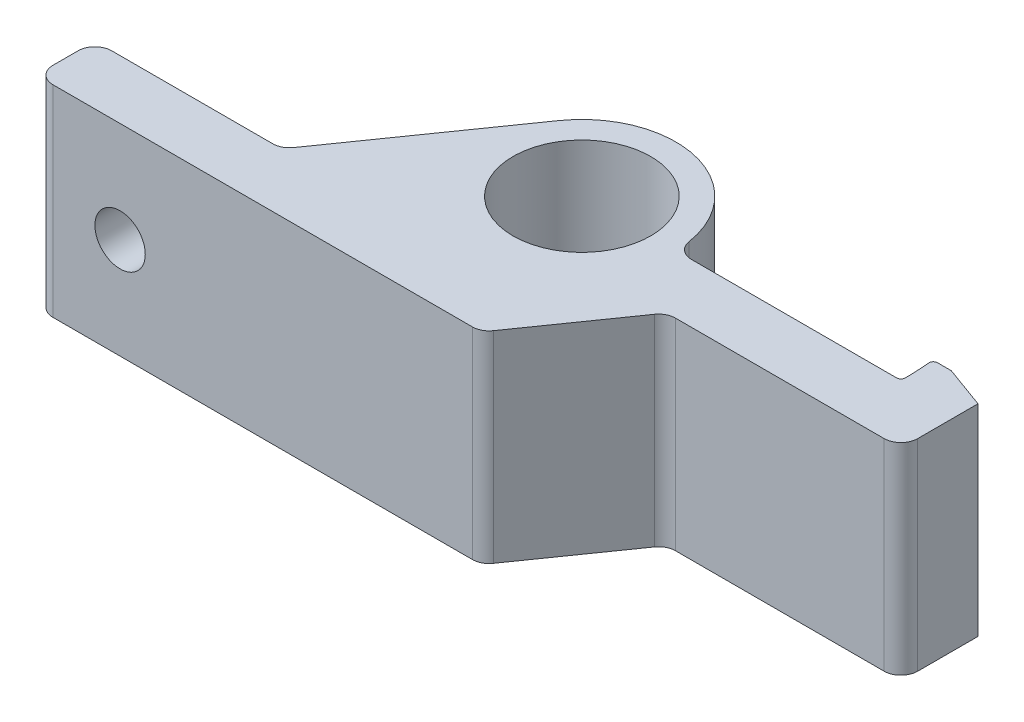
SolidWorks part; units mm, degrees
ref_plane "Front Plane" through (0, 0, 0) normal (0, 0, 1) x (1, 0, 0)
ref_plane "Top Plane" through (0, 0, 0) normal (0, 1, 0) x (1, 0, 0)
ref_plane "Right Plane" through (0, 0, 0) normal (1, 0, 0) x (0, 0, -1)
sketch "Sketch1" plane through (0, 0, 0) normal (0, 1, 0) x (1, 0, 0)
  line L0 (0, 0) -> (26.5, 0)
  line L1 (45, 6.5) -> (45, 12)
  line L2 (45, 12) -> (41.5, 12)
  line L3 (41.5, 12) -> (41.5, 10)
  line L6 (41.5, 10) -> (28.1, 10)
  line L8 (11.1123, 3.5) -> (0, 3.5)
  line L9 (0, 3.5) -> (0, 0)
  line L10 (11.1123, 3.5) -> (17.9127, 13.212)
  line L12 (26.5, 0) -> (31.0513, 6.5)
  line L13 (31.0513, 6.5) -> (45, 6.5)
  circle A0 centre (22.5, 10) radius 4.1
  arc A1 (28.1, 10) -> (17.9127, 13.212) centre (22.5, 10) ccw
  dimension "D3" = 8.2
  dimension "D7" = 125
  dimension "D8" = 3.5
  dimension "D5" = 1.5
  dimension "D2" = 3.5
  dimension "D4" = 10
  dimension "D6" = 3.5
  dimension "D9" = 125
  dimension "D10" = 4
  dimension "D11" = 45
  dimension "D12" = 22.5
  dimension "D14" = 2
extrude "Boss-Extrude1" add sketch "Sketch1" along normal mid plane 12 contours L1 L2 L3 L6 A1 L10 L8 L9 L0 L12 L13 | A0
hole_wizard "Ø3.0mm Dowel Hole1" positions "Sketch2" profile "Sketch3" hole size "Ø3.0" standard "ANSI Metric"
sketch "Sketch2" plane through (0, 0, 0) normal (0, 0, 1) x (1, 0, 0)
  line L0 (0, 6) -> (0, -6) construction
  point P0 (5, 0)
  point P5 (0, 0)
  dimension "D1" = 5
sketch "Sketch3" plane through (5, 0, 0) normal (1, 0, 0) x (0, -1, 0)
  line L0 (0, 0) -> (0, 4.4003)
  line L1 (0, 4.4003) -> (1.5, 3.499)
  line L2 (1.5, 3.499) -> (1.5, 0)
  line L5 (1.5, 0) -> (0, 0)
  line L10 (0, 4.4003) -> (-1.5, 3.499) construction
  line L11 (0, -6.35) -> (0, 107.95) construction
  dimension "Hole Dia." = 3
  dimension "Hole Depth" = 3.499
  dimension "Drill Angle" = 118
sketch "Sketch5" plane through (0, 6, 0) normal (0, 1, 0) x (1, 0, 0)
  line L0 (41.5, 12) -> (41.5, 10.5)
  line L1 (41.5, 12) -> (41.5, 10) construction
  line L2 (41.5, 12) -> (41.4011, 12)
  arc A0 (41.5, 10.5) -> (41.4011, 12) centre (22.5, 10) ccw
  dimension "D1" = 1.5
extrude "Boss-Extrude3" add sketch "Sketch5" against normal up to surface (12 mm away) up to face at (26.2595, -6, -7.3588)
fillet "Fillet1" radius 0.25 2 edges at (41.4011, 0, -12) (41.5, 0, -10)
fillet "Fillet3" radius 1 7 edges at (0, 0, -3.5) (0, 0, 0) (45, 0, -6.5) (31.0513, 0, -6.5) (26.5, 0, 0) (11.1123, 0, -3.5) (28.1, 0, -10)
sketch "Sketch8" plane through (0, 6, 0) normal (0, 1, 0) x (1, 0, 0)
  line L0 (45, 12) -> (42.5, 12)
  line L1 (45, 12) -> (41.6769, 12) construction
  line L2 (42.5, 12) -> (45, 11.0901)
  line L3 (45, 7.5) -> (45, 12) construction
  line L4 (45, 11.0901) -> (45, 12)
  dimension "D1" = 20
  dimension "D2" = 2.5
extrude "Cut-Extrude3" cut sketch "Sketch8" against normal up to surface (12 mm away) up to face at (26.4724, -6, -6.9)
